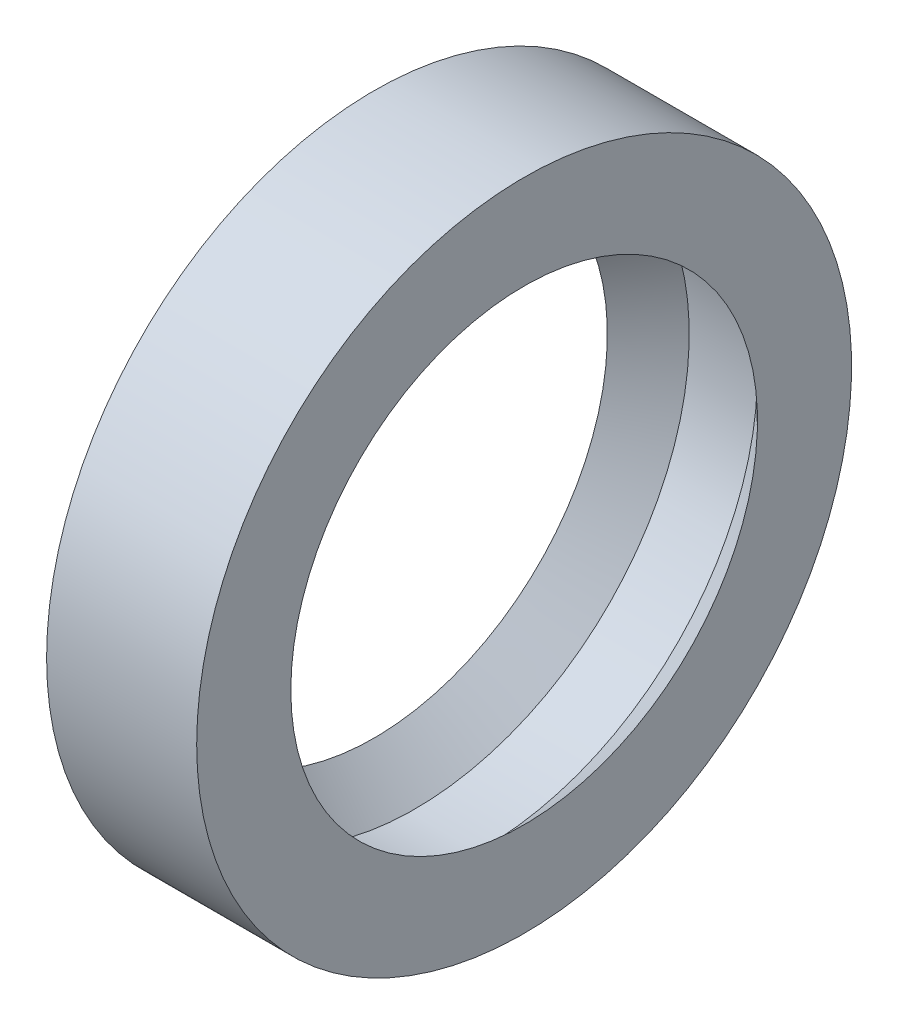
SolidWorks part; units mm, degrees
ref_plane "Front Plane" through (0, 0, 0) normal (0, 0, 1) x (1, 0, 0)
ref_plane "Top Plane" through (0, 0, 0) normal (0, 1, 0) x (1, 0, 0)
ref_plane "Right Plane" through (0, 0, 0) normal (1, 0, 0) x (0, 0, -1)
sketch "Axial profile (mm)" plane through (0, 0, 0) normal (0, 0, 1) x (1, 0, 0)
  line L0 (-110, 0) -> (75, 0) construction
  line L1 (-5, 17.1) -> (-2, 20.1)
  line L2 (-2, 20.1) -> (3, 20.1)
  line L3 (3, 20.1) -> (6, 17.1)
  line L4 (6, 17.1) -> (6, 24)
  line L5 (6, 24) -> (-5, 24)
  line L6 (-5, 24) -> (-5, 17.1)
revolve "Full revolution" add sketch "Axial profile (mm)" angle 360 about L0
